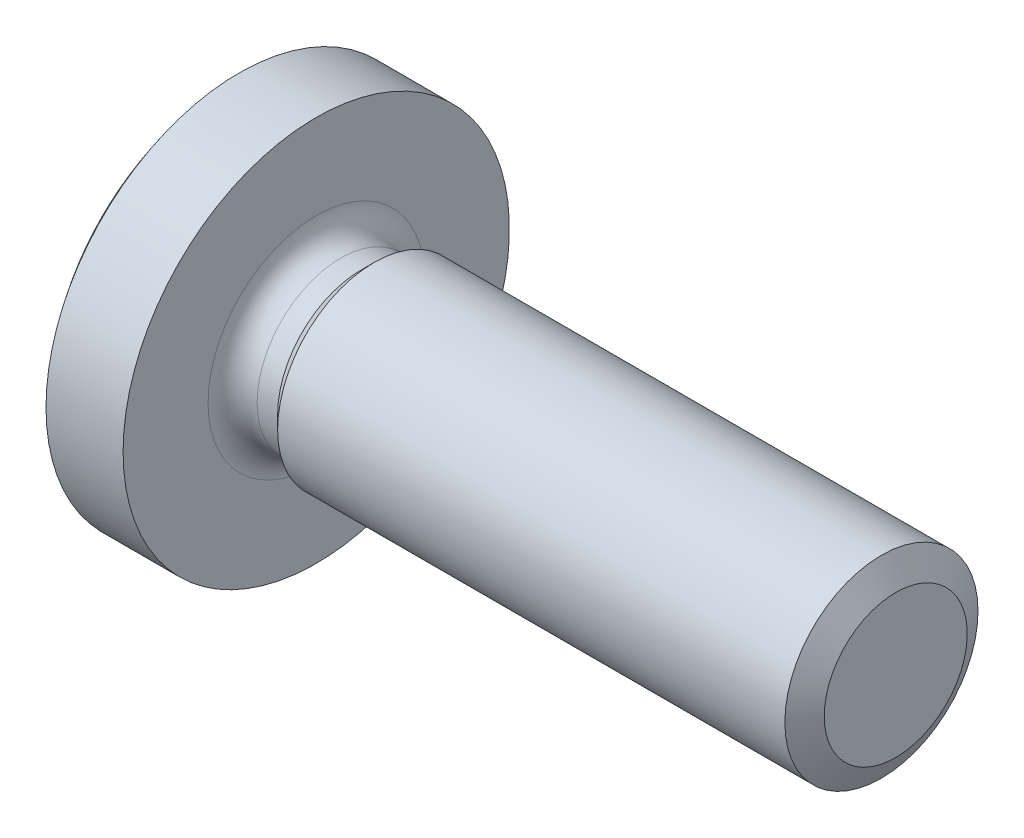
SolidWorks part; units mm, degrees
revolve "基体-旋转" add sketch "草图2" angle 360 about L0
sketch "草图2" plane through (0, 0, 0) normal (0, 0, 1) x (1, 0, 0)
  line L0 (-1.3318, 0) -> (6.5885, 0) construction
  line L1 (0, 0) -> (37.5, 0)
  line L2 (37.5, 0) -> (37.5, 5)
  line L3 (37.5, 5) -> (10.5, 5)
  line L4 (10.5, 5) -> (9.83, 4.33)
  line L5 (9.83, 4.33) -> (8.77, 4.33)
  line L6 (7.5, 5.6) -> (7.5, 10)
  line L7 (7.5, 10) -> (3.51, 10)
  arc A0 (7.5, 5.6) -> (8.77, 4.33) centre (8.77, 5.6) ccw
  arc A1 (0, 0) -> (3.51, 10) centre (16, 0) cw
  dimension "D3" = 16
  dimension "dk" = 20
  dimension "d" = 10
  dimension "l" = 30
  dimension "a" = 3
  dimension "D1" = 45
  dimension "D2" = 8.66
  dimension "da" = 11.2
  dimension "k" = 7.5
cosmetic thread "装饰螺纹线1" parameters "D1"=27, "D2"=8.66
ref_plane "前视" through (0, 0, 0) normal (0, 0, 1) x (1, 0, 0)
ref_plane "上视" through (0, 0, 0) normal (0, 1, 0) x (1, 0, 0)
ref_plane "右视" through (0, 0, 0) normal (1, 0, 0) x (0, 0, -1)
sketch "尺寸草图" plane through (0, 0, 0) normal (0, 0, 1) x (1, 0, 0)
  line L0 (0, 0) -> (30, 0)
  line L1 (0, 0) -> (0, 20)
  line L2 (30, 0) -> (30, 11.2)
  point P5 (0, 10)
  point P6 (28.5, 0)
  point P7 (3, 0)
  point P8 (7.5, 0)
  point P9 (14, 0)
  point P10 (10.1, 0)
  point P11 (24.2, 0)
  dimension "dk" = 20
  dimension "d" = 10
  dimension "l" = 30
  dimension "a" = 3
  dimension "da" = 11.2
  dimension "k" = 7.5
  dimension "P" = 1.5
  dimension "rf" = 16
  dimension "m" = 10.1
  dimension "h" = 5.8
sketch "草图3" plane through (0, 0, 0) normal (0, 0, 1) x (1, 0, 0)
  line L0 (36.7581, 5) -> (38.2581, 5)
  line L1 (38.2581, 5) -> (37.5, 3.701)
  line L2 (37.5, 3.701) -> (36.7581, 5)
  line L3 (37.5, 5) -> (10.5, 5) construction
  line L4 (37.5, -5) -> (37.5, 5) construction
  line L5 (-0.2428, 0) -> (7.1644, 0) construction
  line L6 (-1.3318, 0) -> (6.5885, 0) construction
  dimension "P" = 1.5
  dimension "D1" = 1.299
  dimension "D2" = 60
revolve "切除-旋转1" cut sketch "草图3" angle 360 about L5
sketch "草图5" plane through (0, 0, 0) normal (1, 0, 0) x (0, 0, -1)
  line L1 (0.75, 5.05) -> (-0.75, 5.05)
  line L2 (0.75, 5.05) -> (0.75, -5.05)
  line L3 (0.75, -5.05) -> (-0.75, -5.05)
  line L4 (-0.75, 5.05) -> (-0.75, -5.05)
  point P4 (0.75, 0)
  point P5 (0, 5.05)
  dimension "m" = 10.1
  dimension "D1" = 1.5
ref_plane "基准面1" through (5.8, 0, 0) normal (1, 0, 0) x (0, 0, -1)
pattern_linear "阵列(线性)1" [suppressed] count 19 spacing 1.5 along (1, 0, 0)
sketch "草图6" plane through (5.8, 0, 0) normal (1, 0, 0) x (0, 0, -1)
  point P0 (0, 0)
loft "切除-放样1" cut profiles "草图6", "草图5"
ref_plane "基准面2" through (0, 0, 0) normal (0, -0.7071, 0.7071) x (1, 0, 0)
mirror "镜向1" about plane through (0, 0, 0) normal (0, -0.7071, 0.7071) of "切除-放样1"
equation "\"l@草图2\" = \"l@尺寸草图\""
equation "\"dk@草图2\" = \"dk@尺寸草图\""
equation "\"k@草图2\" = \"k@尺寸草图\""
equation "\"D2@草图2\" = \"d@尺寸草图\"*0.866"
equation "\"a@草图2\" = \"a@尺寸草图\""
equation "\"D3@草图2\" = \"rf@尺寸草图\""
equation "\"d@草图2\" = \"d@尺寸草图\""
equation "\"da@草图2\" = \"da@尺寸草图\""
equation "\"D2@装饰螺纹线1\" = \"d@尺寸草图\"*0.866"
equation "\"D1@装饰螺纹线1\" = \"l@尺寸草图\"-\"a@尺寸草图\""
equation "\"P@草图3\" = \"P@尺寸草图\""
equation "\"D1@草图3\" = \"P@尺寸草图\"*0.866"
equation "\"h@基准面1\" = \"h@尺寸草图\""
equation "\"D1@草图5\" = \"P@尺寸草图\""
equation "\"m@草图5\" = \"m@尺寸草图\""
equation "\"D3@阵列(线性)1\" = \"P@尺寸草图\""
equation "\"D1@阵列(线性)1\" = (\"l@尺寸草图\"-\"a@尺寸草图\")/\"P@尺寸草图\"+1"
